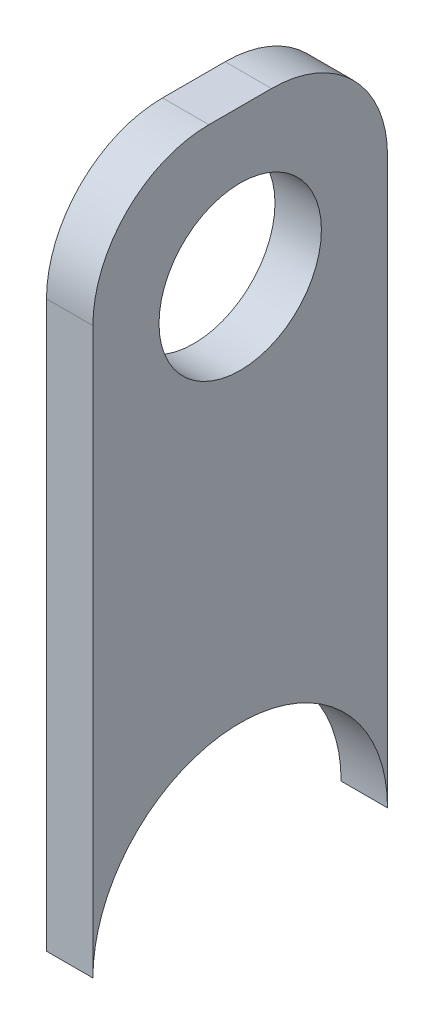
SolidWorks part; units mm, degrees
ref_plane "Front Plane" through (0, 0, 0) normal (0, 0, 1) x (1, 0, 0)
ref_plane "Top Plane" through (0, 0, 0) normal (0, 1, 0) x (1, 0, 0)
ref_plane "Right Plane" through (0, 0, 0) normal (1, 0, 0) x (0, 0, -1)
sketch "Sketch1" plane through (0, 0, 0) normal (1, 0, 0) x (0, 0, -1)
  line L0 (-12.7, 0) -> (-12.7, 48.71)
  line L1 (12.7, 0) -> (12.7, 48.71)
  line L2 (2.7, 58.71) -> (-2.7, 58.71)
  arc A0 (12.7, 0) -> (-12.7, 0) centre (0, 0) ccw
  arc A1 (2.7, 58.71) -> (12.7, 48.71) centre (2.7, 48.71) cw
  arc A2 (-2.7, 58.71) -> (-12.7, 48.71) centre (-2.7, 48.71) ccw
  circle A3 centre (0, 46.01) radius 7
  point P11 (-12.7, 58.71)
  dimension "D1" = 25.4
  dimension "D3" = 10
  dimension "D5" = 14
  dimension "D2" = 58.71
  dimension "D4" = 46.01
extrude "Boss-Extrude1" add sketch "Sketch1" along normal blind 4
